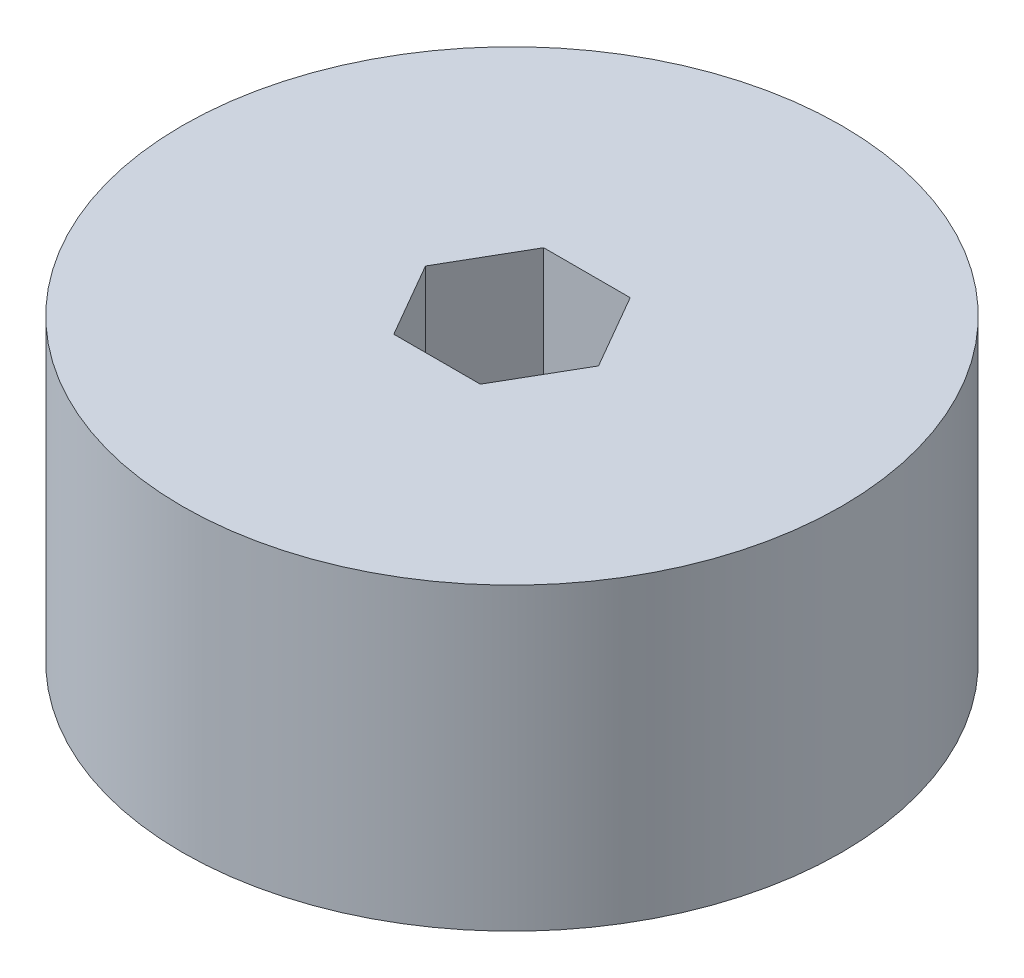
SolidWorks part; units mm, degrees
ref_plane "Front Plane" through (0, 0, 0) normal (0, 0, 1) x (1, 0, 0)
ref_plane "Top Plane" through (0, 0, 0) normal (0, 1, 0) x (1, 0, 0)
ref_plane "Right Plane" through (0, 0, 0) normal (1, 0, 0) x (0, 0, -1)
sketch "Sketch1" plane through (0, 0, 0) normal (0, 1, 0) x (1, 0, 0)
  circle A0 centre (0, 0) radius 27.94
  dimension "D1" = 55.88
extrude "Boss-Extrude1" add sketch "Sketch1" along normal blind 25.4
sketch "Sketch2" plane through (0, 0, 0) normal (0, -1, 0) x (1, 0, 0)
  line L1 (-3.6662, 6.35) -> (-7.3323, 0)
  line L2 (-7.3323, 0) -> (-3.6662, -6.35)
  line L3 (-3.6662, -6.35) -> (3.6662, -6.35)
  line L4 (3.6662, -6.35) -> (7.3323, 0)
  line L5 (7.3323, 0) -> (3.6662, 6.35)
  line L6 (3.6662, 6.35) -> (-3.6662, 6.35)
  circle A0 centre (0, 0) radius 6.35 construction
  point P1 (5.3263, 5.0393)
  point P10 (6.8471, 2.6231)
  point P11 (7.3323, 0)
  dimension "D1" = 12.7
extrude "Cut-Extrude1" cut sketch "Sketch2" against normal through all contours L1 L2 L3 L4 L5 L6
